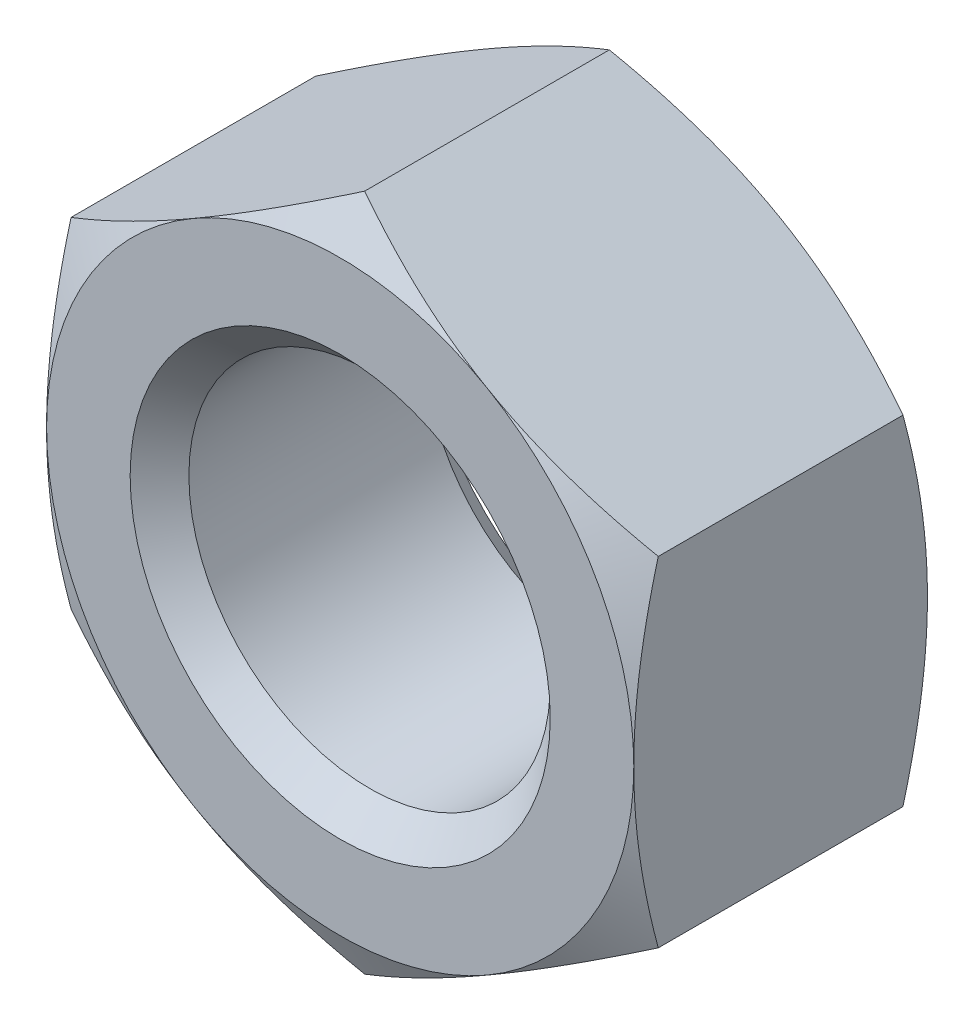
SolidWorks part; units mm, degrees
material "Plain Carbon Steel"
ref_plane "Front Plane" through (0, 0, 0) normal (0, 0, 1) x (1, 0, 0)
ref_plane "Top Plane" through (0, 0, 0) normal (0, 1, 0) x (1, 0, 0)
ref_plane "Right Plane" through (0, 0, 0) normal (1, 0, 0) x (0, 0, -1)
sketch "Sketch1" plane through (0, 0, 0) normal (0, 0, 1) x (1, 0, 0)
  line L1 (0, -7.5056) -> (6.5, -3.7528)
  line L2 (6.5, -3.7528) -> (6.5, 3.7528)
  line L3 (6.5, 3.7528) -> (0, 7.5056)
  line L4 (0, 7.5056) -> (-6.5, 3.7528)
  line L5 (-6.5, 3.7528) -> (-6.5, -3.7528)
  line L6 (-6.5, -3.7528) -> (0, -7.5056)
  circle A0 centre (0, 0) radius 6.5 construction
  circle A1 centre (0, 0) radius 4
  dimension "D2" = 8
  dimension "D1" = 13
extrude "Boss-Extrude1" add sketch "Sketch1" along normal blind 6.5
sketch "Sketch2" plane through (0, 0, 0) normal (1, 0, 0) x (0, 0, -1)
  line L0 (-6.5, 7.5056) -> (-6.5, 6.5)
  line L1 (-6.5, 3.7528) -> (-6.5, 7.5056) construction
  line L2 (-6.5, 6.5) -> (-5.9583, 7.5056)
  line L3 (-6.5, 7.5056) -> (0, 7.5056) construction
  line L4 (-5.9583, 7.5056) -> (-6.5, 7.5056)
  line L5 (-0.5417, 7.5056) -> (0, 7.5056)
  line L6 (0, 7.5056) -> (0, 6.5)
  line L7 (0, 3.7528) -> (0, 7.5056) construction
  line L8 (0, 6.5) -> (-0.5417, 7.5056)
  line L9 (-5.9583, 7.5056) -> (-5.4167, 7.5056) construction
  line L10 (-5.4167, 7.5056) -> (-4.875, 7.5056) construction
  line L11 (-4.875, 7.5056) -> (-4.3333, 7.5056) construction
  line L12 (-4.3333, 7.5056) -> (-3.7917, 7.5056) construction
  line L13 (-3.7917, 7.5056) -> (-3.25, 7.5056) construction
  line L14 (-3.25, 7.5056) -> (-2.7083, 7.5056) construction
  line L15 (-2.7083, 7.5056) -> (-2.1667, 7.5056) construction
  line L16 (-2.1667, 7.5056) -> (-1.625, 7.5056) construction
  line L17 (-1.625, 7.5056) -> (-1.0833, 7.5056) construction
  line L18 (0, 0) -> (-6.5, 0) construction
  line L19 (-6.5, -3.7528) -> (-6.5, 3.7528) construction
  line L20 (-6.5, 4) -> (-5.85, 4)
  line L21 (-5.85, 4) -> (-6.5, 4.65)
  line L22 (-6.5, 4.65) -> (-6.5, 4)
  line L23 (0, 4) -> (-0.65, 4)
  line L24 (0, -3.7528) -> (0, 3.7528) construction
  line L25 (-0.65, 4) -> (0, 4.65)
  line L26 (0, 4.65) -> (0, 4)
  line L29 (-5.85, 4) -> (-5.2, 4) construction
  line L30 (-5.2, 4) -> (-4.55, 4) construction
  line L31 (-4.55, 4) -> (-3.9, 4) construction
  line L32 (-3.9, 4) -> (-3.25, 4) construction
  line L33 (-3.25, 4) -> (-2.6, 4) construction
  line L34 (-2.6, 4) -> (-1.95, 4) construction
  line L35 (-1.95, 4) -> (-1.3, 4) construction
  line L36 (-1.3, 4) -> (-0.65, 4) construction
  line L37 (-1.0833, 7.5056) -> (-0.5417, 7.5056) construction
  dimension "D1" = 13
revolve "Cut-Revolve1" cut sketch "Sketch2" angle 360 about L18
